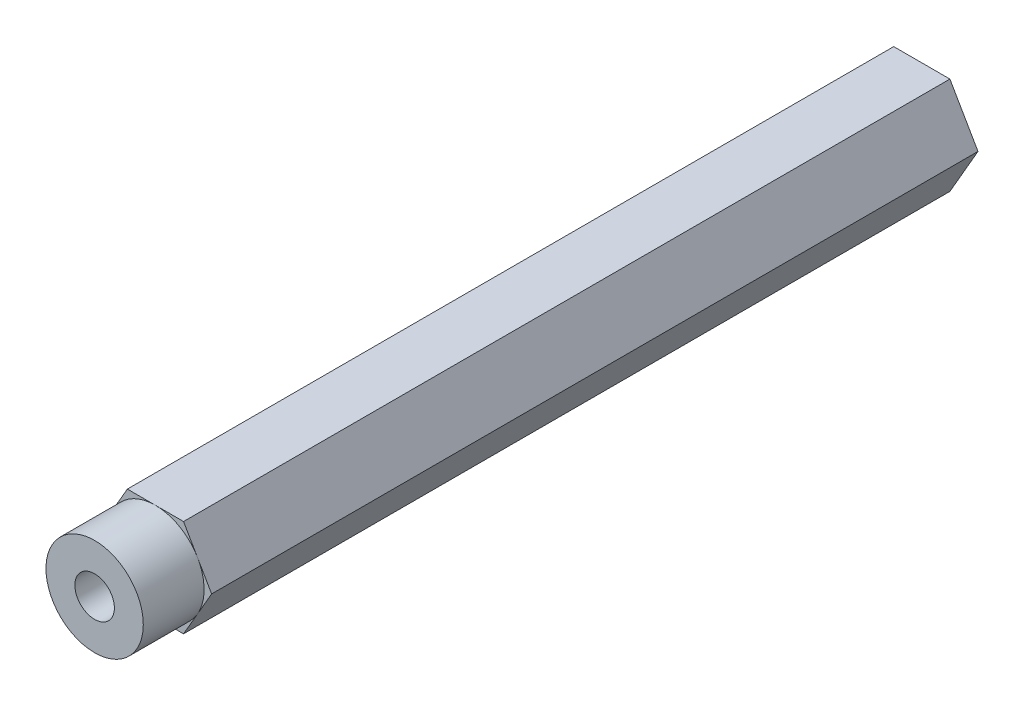
SolidWorks part; units mm, degrees
ref_plane "Front Plane" through (0, 0, 0) normal (0, 0, 1) x (1, 0, 0)
ref_plane "Top Plane" through (0, 0, 0) normal (0, 1, 0) x (1, 0, 0)
ref_plane "Right Plane" through (0, 0, 0) normal (1, 0, 0) x (0, 0, -1)
sketch "Sketch1" plane through (0, 0, 0) normal (0, 0, 1) x (1, 0, 0)
  line L1 (7.3323, 0) -> (3.6662, 6.35)
  line L2 (3.6662, 6.35) -> (-3.6662, 6.35)
  line L3 (-3.6662, 6.35) -> (-7.3323, 0)
  line L4 (-7.3323, 0) -> (-3.6662, -6.35)
  line L5 (-3.6662, -6.35) -> (3.6662, -6.35)
  line L6 (3.6662, -6.35) -> (7.3323, 0)
  circle A0 centre (0, 0) radius 6.35 construction
  circle A1 centre (0, 0) radius 2.5797
  dimension "D1" = 12.7
  dimension "D2" = 5.1594
extrude "Boss-Extrude1" add sketch "Sketch1" along normal blind 100.0125
sketch "Sketch2" plane through (0, 0, 100.0125) normal (0, 0, 1) x (1, 0, 0)
  circle A0 centre (0, 0) radius 2.5797
  circle A1 centre (0, 0) radius 6.35
  dimension "D1" = 12.7
  dimension "D2" = 5.1594
extrude "Boss-Extrude2" add sketch "Sketch2" along normal blind 7.9375
